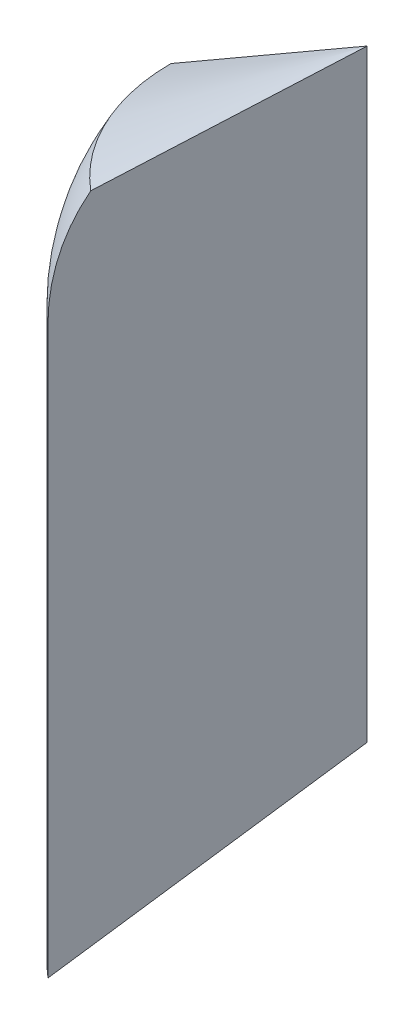
SolidWorks part; units mm, degrees
other "Markup1"
sketch "Sketch2" plane through (-30480, 106680, 23349.0346) normal (-0.2103, 0.1343, 0.9684) x (0.9773, 0.0022, 0.2119)
ref_plane "Front Plane" through (0, 0, 0) normal (0, 0, 1) x (1, 0, 0)
ref_plane "Top Plane" through (0, 0, 0) normal (0, 1, 0) x (1, 0, 0)
ref_plane "Right Plane" through (0, 0, 0) normal (1, 0, 0) x (0, 0, -1)
sketch "Sketch1" plane through (0, 0, 0) normal (0, 0, 1) x (1, 0, 0)
  line L1 (0, 0) -> (0, 13766.3804) construction
  line L2 (0, 106680) -> (-26396.4543, 91440)
  line L3 (0, 106680) -> (0, 25575.7568)
  line L5 (0, 0) -> (-30480, 0) construction
  line L6 (-30480, 0) -> (-30480, 76200)
  line L7 (0, 25575.7568) -> (-30480, 0)
  arc A1 (-30480, 76200) -> (-26396.4543, 91440) centre (0, 76200) cw
  dimension "D1" = 30480
  dimension "D3" = 30
  dimension "D2" = 40
  dimension "D4" = 76200
  dimension "D5" = 30480
  dimension "D6" = 106680
revolve "Revolve1" add sketch "Sketch1" angle 50 about L1
equation "\"Radius\"= 100ft"
equation "\"Pile Height\"= 100ft + \"Stem Wall Height\""
equation "\"Angle of Repose\"= 30"
equation "\"Shear Angle\"= 40"
equation "\"Angle of Rotation\"=50"
equation "\"D1@Revolve1\"=\"Angle of Rotation\""
equation "\"D1@Sketch1\"=\"Radius\""
equation "\"D3@Sketch1\"=\"Angle of Repose\""
equation "\"D2@Sketch1\"=\"Shear Angle\""
equation "\"D5@Sketch1\"=\"Radius\""
equation "\"D6@Sketch1\"=\"Pile Height\""
equation "\"Stem Wall Height\"= 250"
equation "\"D4@Sketch1\"=\"Stem Wall Height\""
